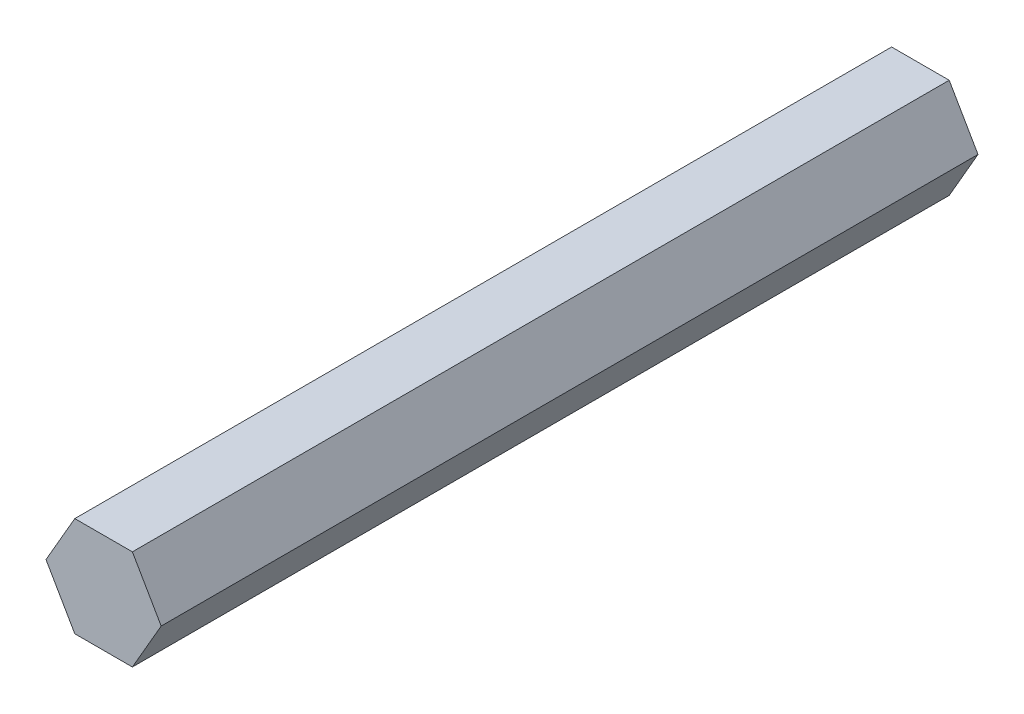
SolidWorks part; units mm, degrees
ref_plane "Front Plane" through (0, 0, 0) normal (0, 0, 1) x (1, 0, 0)
ref_plane "Top Plane" through (0, 0, 0) normal (0, 1, 0) x (1, 0, 0)
ref_plane "Right Plane" through (0, 0, 0) normal (1, 0, 0) x (0, 0, -1)
sketch "Sketch1" plane through (0, 0, 0) normal (0, 0, 1) x (1, 0, 0)
  line L1 (7.3323, 0) -> (3.6662, 6.35)
  line L2 (3.6662, 6.35) -> (-3.6662, 6.35)
  line L3 (-3.6662, 6.35) -> (-7.3323, 0)
  line L4 (-7.3323, 0) -> (-3.6662, -6.35)
  line L5 (-3.6662, -6.35) -> (3.6662, -6.35)
  line L6 (3.6662, -6.35) -> (7.3323, 0)
  circle A0 centre (0, 0) radius 6.35 construction
extrude "Boss-Extrude1" add sketch "Sketch1" along normal blind 104
